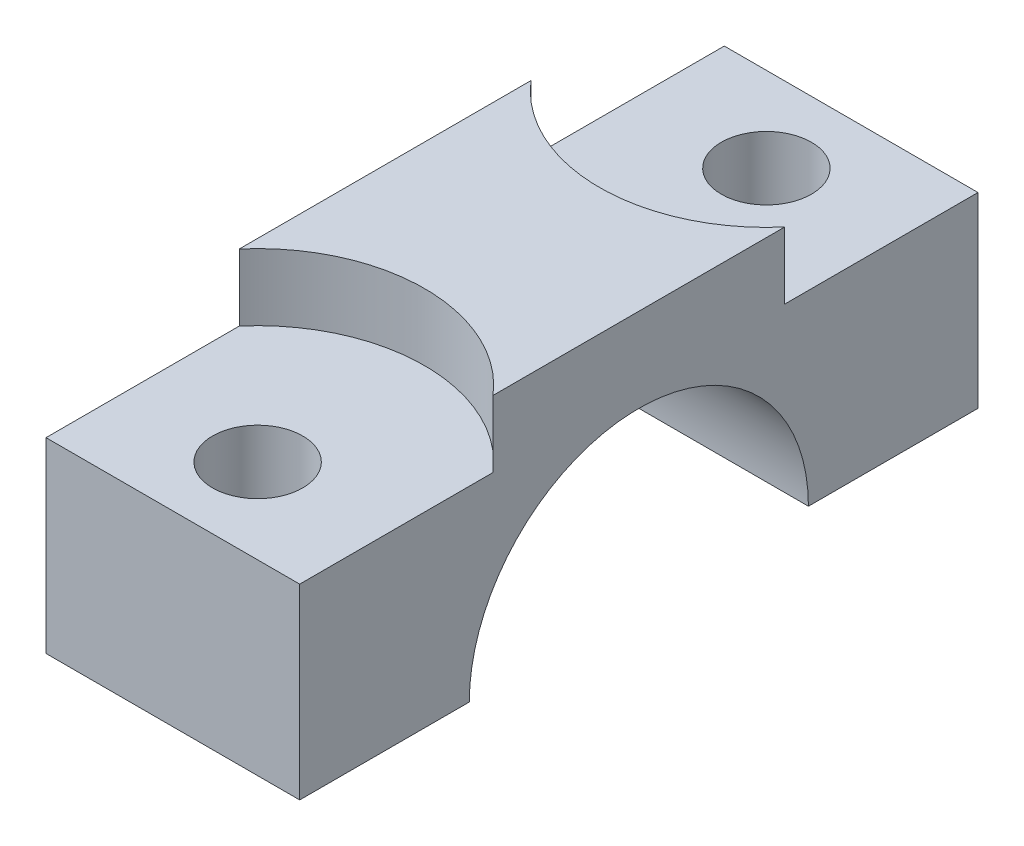
SolidWorks part; units mm, degrees
ref_plane "Front Plane" through (0, 0, 0) normal (0, 0, 1) x (1, 0, 0)
ref_plane "Top Plane" through (0, 0, 0) normal (0, 1, 0) x (1, 0, 0)
ref_plane "Right Plane" through (0, 0, 0) normal (1, 0, 0) x (0, 0, -1)
sketch "Sketch2" plane through (0, 0, 0) normal (1, 0, 0) x (0, 0, -1)
  line L0 (12.7, 0) -> (25.4, 0)
  line L1 (-25.4, 19) -> (25.4, 19)
  line L2 (-25.4, 19) -> (-25.4, 0)
  line L3 (-25.4, 0) -> (-12.7, 0)
  line L4 (25.4, 19) -> (25.4, 0)
  arc A0 (-12.7, 0) -> (12.7, 0) centre (0, 0) cw
  point P4 (0, 0)
  point P9 (0, 0)
  point P10 (0, 19)
  point P11 (0, 0)
  dimension "D3" = 12.7
  dimension "D1" = 50.8
  dimension "D2" = 19
extrude "Boss-Extrude1" add sketch "Sketch2" along normal mid plane 19
sketch "Sketch3" plane through (0, 0, 0) normal (0, -1, 0) x (1, 0, 0)
  line L0 (-9.5, 19.05) -> (9.5, 19.05) construction
  line L1 (-9.5, 25.4) -> (-9.5, 12.7) construction
  line L2 (9.5, 25.4) -> (9.5, 12.7) construction
  line L3 (-9.5, -19.05) -> (9.5, -19.05) construction
  line L4 (-9.5, -12.7) -> (-9.5, -25.4) construction
  line L5 (9.5, -12.7) -> (9.5, -25.4) construction
  point P12 (0, 19.05)
  point P13 (0, -19.05)
hole_wizard "CBORE for M12 Hex Head Cap Screw1" positions "Sketch4" profile "Sketch5" counterbore size "M12" standard "ISO" end condition through all
sketch "Sketch4" plane through (0, 19, 0) normal (0, 1, 0) x (1, 0, 0)
  point P0 (0, 19.05)
  point P3 (0, -19.05)
sketch "Sketch5" plane through (0, 19, -19.05) normal (1, 0, 0) x (0, 0, 1)
  line L0 (0, 0) -> (0, 19)
  line L1 (0, 19) -> (3.375, 19)
  line L3 (3.375, 19) -> (3.375, 5)
  line L4 (3.375, 5) -> (12.5, 5)
  line L5 (12.5, 5) -> (12.5, 0)
  line L7 (12.5, 0) -> (0, 0)
  line L11 (0, -6.35) -> (0, 107.95) construction
  dimension "Thru Hole Dia." = 6.75
  dimension "Thru Hole Depth" = 19
  dimension "C'Bore Dia." = 25
  dimension "C'Bore Depth" = 5
